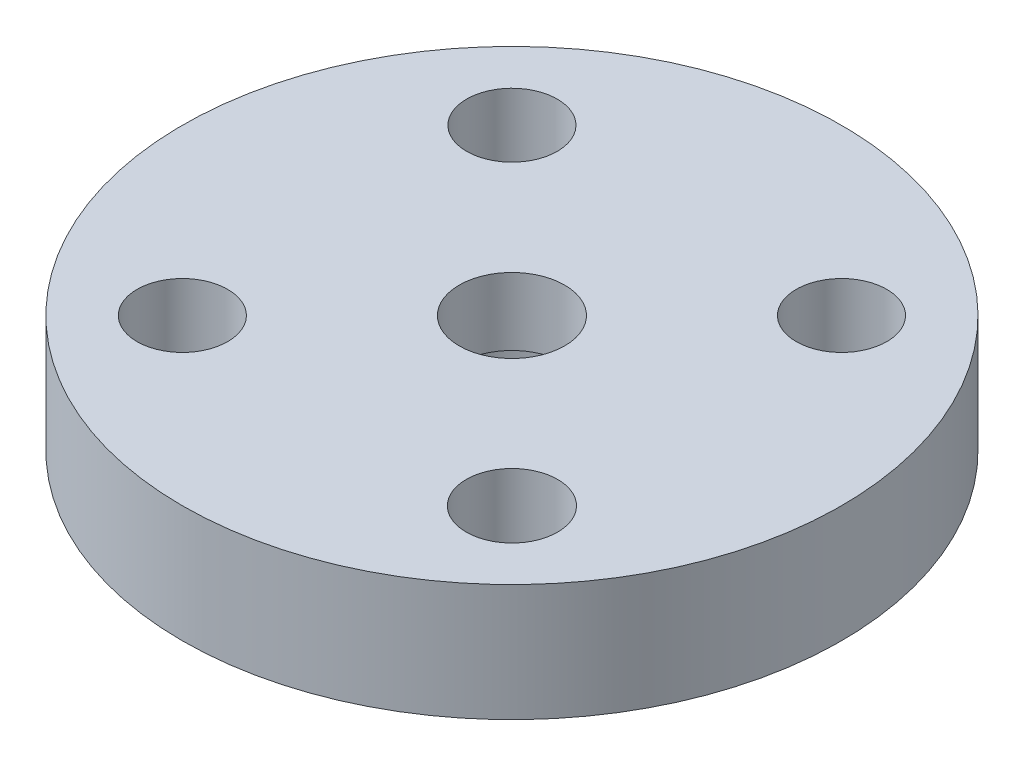
SolidWorks part; units mm, degrees
ref_plane "Front Plane" through (0, 0, 0) normal (0, 0, 1) x (1, 0, 0)
ref_plane "Top Plane" through (0, 0, 0) normal (0, 1, 0) x (1, 0, 0)
ref_plane "Right Plane" through (0, 0, 0) normal (1, 0, 0) x (0, 0, -1)
sketch "Sketch1" plane through (0, 0, 0) normal (0, 1, 0) x (1, 0, 0)
  line L1 (-5, -5) -> (5, -5) construction
  line L2 (-5, -5) -> (-5, 5) construction
  line L3 (-5, 5) -> (5, 5) construction
  line L4 (5, -5) -> (5, 5) construction
  line L5 (-5, -5) -> (5, 5) construction
  line L6 (-5, 5) -> (5, -5) construction
  circle A0 centre (0, 0) radius 10
  circle A1 centre (0, 0) radius 1.6
  circle A2 centre (-5, -5) radius 1.375
  circle A3 centre (5, -5) radius 1.3864
  circle A5 centre (5, 5) radius 1.375
  circle A7 centre (-5, 5) radius 1.375
  dimension "D1" = 20
  dimension "D2" = 3.2
  dimension "D5" = 2.75
  dimension "D6" = 2.75
  dimension "D7" = 2.75
  dimension "D3" = 45
  dimension "D4" = 10
extrude "Boss-Extrude1" add sketch "Sketch1" along normal blind 3.55
sketch "Sketch2" plane through (0, 0, 0) normal (0, 0, 1) x (1, 0, 0)
  line L0 (-2.8, 1.5) -> (-4.5, 1.5)
  line L1 (-4.5, 1.5) -> (-4.5, -2)
  line L2 (-4.5, -2) -> (-2.8, -2)
  line L3 (-2.8, 1.5) -> (-2.8, -2)
  line L5 (0, 0) -> (0, -2.0483) construction
  dimension "D1" = 4.5
  dimension "D2" = 2.8
  dimension "D3" = 3.5
  dimension "D4" = 2
revolve "Revolve1" add sketch "Sketch2" angle 360 about L5
sketch "Sketch3" plane through (0, 0, 0) normal (0, -1, 0) x (1, 0, 0)
  circle A0 centre (0, 0) radius 2.8
extrude "Cut-Extrude1" cut sketch "Sketch3" against normal blind 1.5
